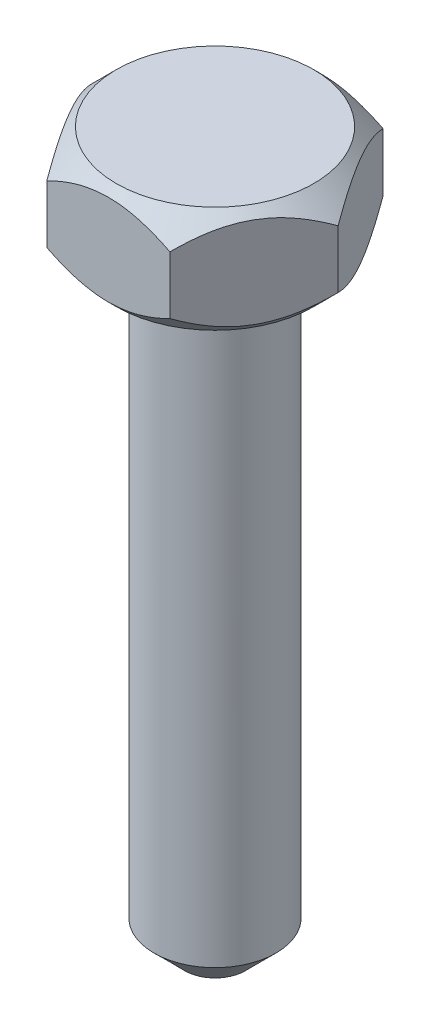
SolidWorks part; units mm, degrees
ref_plane "Спереди" through (0, 0, 0) normal (0, 0, 1) x (1, 0, 0)
ref_plane "Сверху" through (0, 0, 0) normal (0, 1, 0) x (1, 0, 0)
ref_plane "Справа" through (0, 0, 0) normal (1, 0, 0) x (0, 0, -1)
sketch "Эскиз1" plane through (0, 0, 0) normal (0, 1, 0) x (1, 0, 0)
  line L0 (-2.0207, 3.5) -> (2.0207, 3.5)
  line L1 (2.0207, 3.5) -> (4.0415, 0)
  line L2 (4.0415, 0) -> (2.0207, -3.5)
  line L3 (2.0207, -3.5) -> (-2.0207, -3.5)
  line L4 (-2.0207, -3.5) -> (-4.0415, 0)
  line L5 (-4.0415, 0) -> (-2.0207, 3.5)
  dimension "D5" = 3.5
  dimension "D2" = 120
  dimension "D3" = 120
  dimension "D4" = 120
  dimension "D6" = 3.5
  dimension "D7" = 3.5
  dimension "D8" = 3.5
  dimension "D9" = 3.5
  dimension "D10" = 120
  dimension "D11" = 3.5
extrude "Вытянуть1" add sketch "Эскиз1" against normal blind 3.5
sketch "Эскиз5" plane through (0, -3.5, 0) normal (0, -1, 0) x (1, 0, 0)
  circle A0 centre (0, 0) radius 2
  dimension "D1" = 4
extrude "Вытянуть2" add sketch "Эскиз5" along normal blind 20
chamfer "Фаска1" distance 1 angle 45 1 edges at (0, -23.5, -2)
ref_axis "Ось1" through (0, -3.5, 0) along (0, -1, 0)
ref_plane "Плоскость1" through (0, 0, 0) normal (0, 0, 1) x (1, 0, 0)
sketch "Эскиз4" plane through (0, 0, 0) normal (0, 0, 1) x (1, 0, 0)
  line L0 (-4.0415, -0.8) -> (-3.2415, 0)
  line L1 (-4.0415, -3.5) -> (-4.0415, 0) construction
  line L2 (-4.0415, 0) -> (-2.0207, 0) construction
  line L3 (-3.2415, 0) -> (-4.0415, 0)
  line L4 (-4.0415, 0) -> (-4.0415, -0.8)
  line L5 (-4.0415, -2.7) -> (-3.2415, -3.5)
  line L6 (-4.0415, -3.5) -> (-2.0207, -3.5) construction
  line L7 (-3.2415, -3.5) -> (-4.0415, -3.5)
  line L8 (-4.0415, -3.5) -> (-4.0415, -2.7)
  dimension "D1" = 0.8
  dimension "D2" = 0.8
  dimension "D3" = 0.8
  dimension "D4" = 0.8
revolve "Вырез-Повернуть1" cut sketch "Эскиз4" angle 360 about axis through (0, -3.5, 0) along (0, -1, 0)
